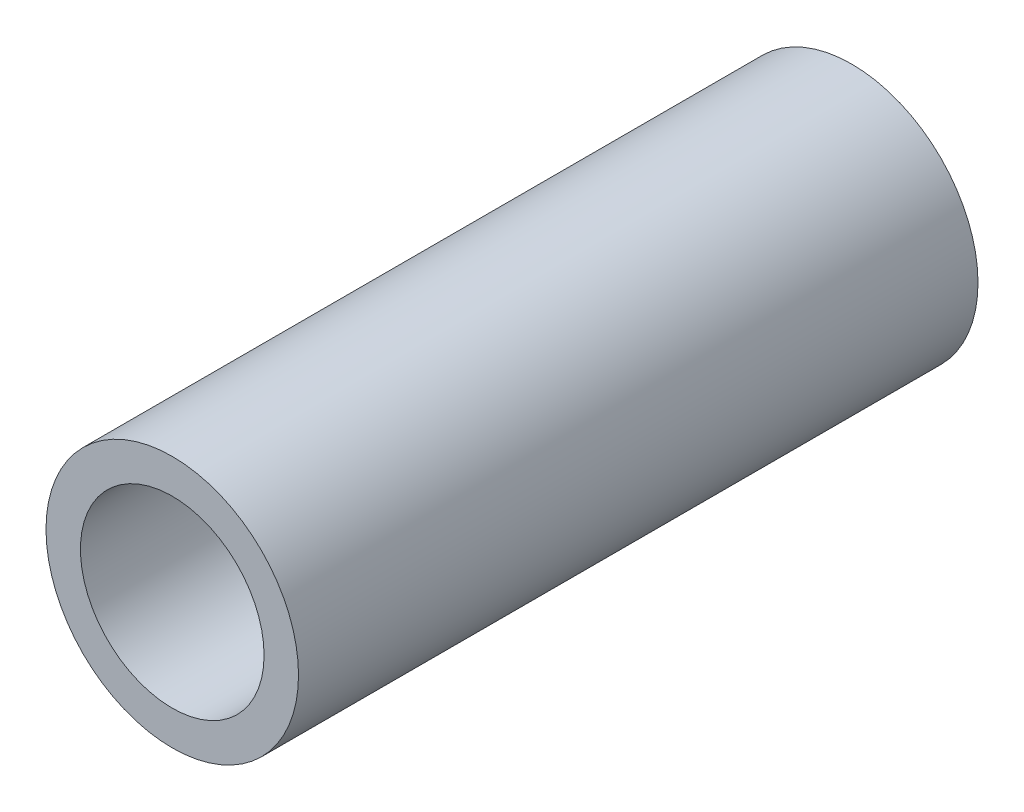
SolidWorks part; units mm, degrees
ref_plane "前视基准面" through (0, 0, 0) normal (0, 0, 1) x (1, 0, 0)
ref_plane "上视基准面" through (0, 0, 0) normal (0, 1, 0) x (1, 0, 0)
ref_plane "右视基准面" through (0, 0, 0) normal (1, 0, 0) x (0, 0, -1)
sketch "草图1" plane through (0, 0, 0) normal (0, 0, 1) x (1, 0, 0)
  circle A0 centre (0, 0) radius 2
  circle A1 centre (0, 0) radius 2.75
  dimension "D1" = 5.5
extrude "凸台-拉伸1" add sketch "草图1" against normal blind 14.8
